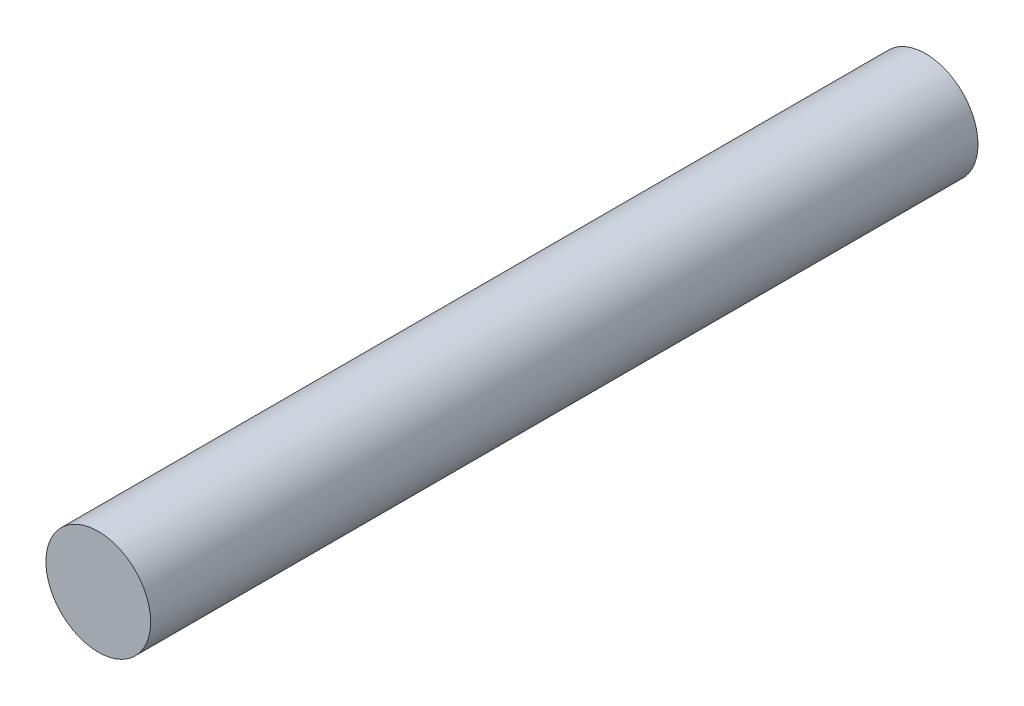
SolidWorks part; units mm, degrees
ref_plane "Płaszczyzna przednia" through (0, 0, 0) normal (0, 0, 1) x (1, 0, 0)
ref_plane "Płaszczyzna górna" through (0, 0, 0) normal (0, 1, 0) x (1, 0, 0)
ref_plane "Płaszczyzna prawa" through (0, 0, 0) normal (1, 0, 0) x (0, 0, -1)
sketch "Sketch1" plane through (0, 0, 0) normal (0, 0, 1) x (1, 0, 0)
  circle A0 centre (-0.246, 0) radius 1
  dimension "D1" = 2
extrude "Boss-Extrude1" add sketch "Sketch1" along normal mid plane 15.8
